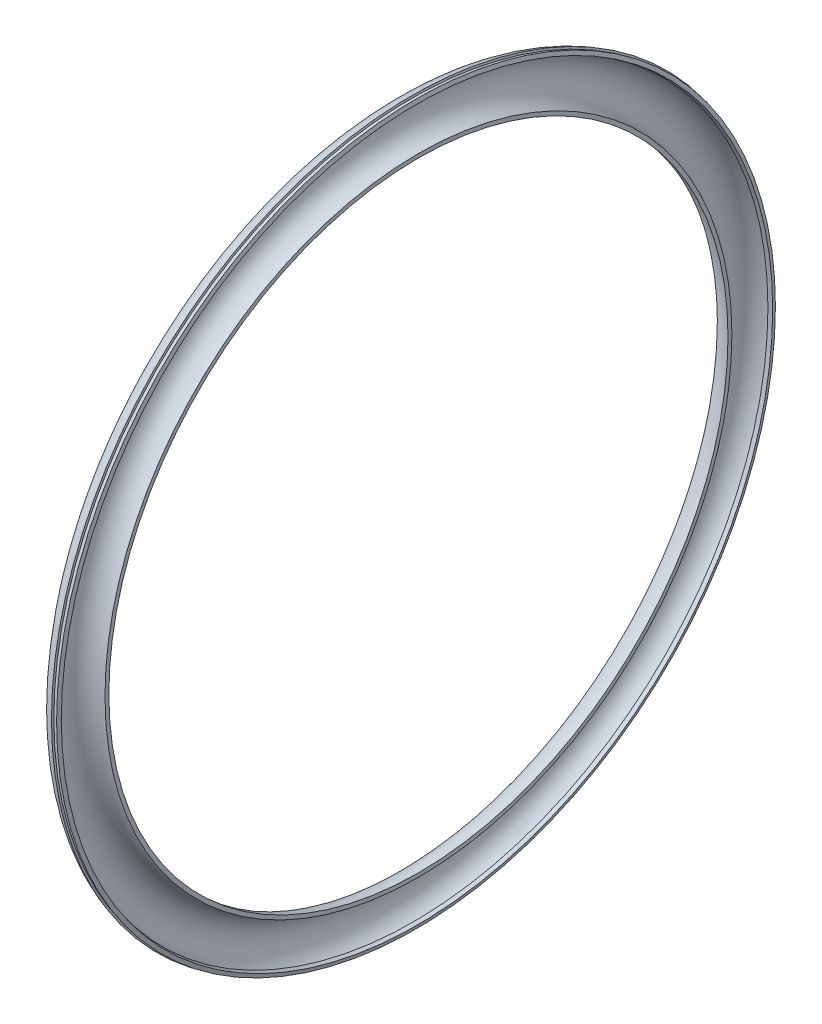
SolidWorks part; units mm, degrees
ref_plane "Front Plane" through (0, 0, 0) normal (0, 0, 1) x (1, 0, 0)
ref_plane "Top Plane" through (0, 0, 0) normal (0, 1, 0) x (1, 0, 0)
ref_plane "Right Plane" through (0, 0, 0) normal (1, 0, 0) x (0, 0, -1)
sketch "Sketch1" plane through (0, 0, 0) normal (0, 0, 1) x (1, 0, 0)
  line L0 (157.4385, 0) -> (-157.4385, 0) construction
  line L1 (0, 0) -> (0, 260) construction
  line L2 (0, 260) -> (-4.3999, 276.4207) construction
  line L3 (-5.1764, 279.3185) -> (-5.9845, 282.3345) construction
  line L4 (-5.1764, 279.3185) -> (-4.7882, 277.8696)
  line L5 (-4.0117, 274.9719) -> (-1.1139, 275.7483)
  line L6 (-1.1139, 275.7483) -> (-1.8904, 278.6461)
  line L7 (-1.8904, 278.6461) -> (-4.7882, 277.8696)
  line L8 (-4.3999, 276.4207) -> (-4.0117, 274.9719)
  line L9 (-4.7882, 277.8696) -> (-5.1764, 279.3185) construction
  line L10 (0, 243) -> (0, 240)
  arc A0 (-5.1764, 279.3185) -> (0, 240) centre (0, 260) ccw
  arc A1 (-4.3999, 276.4207) -> (0, 243) centre (0, 260) ccw
  point P4 (0, 0)
revolve "Revolve1" add sketch "Sketch1" angle 360 about L0
